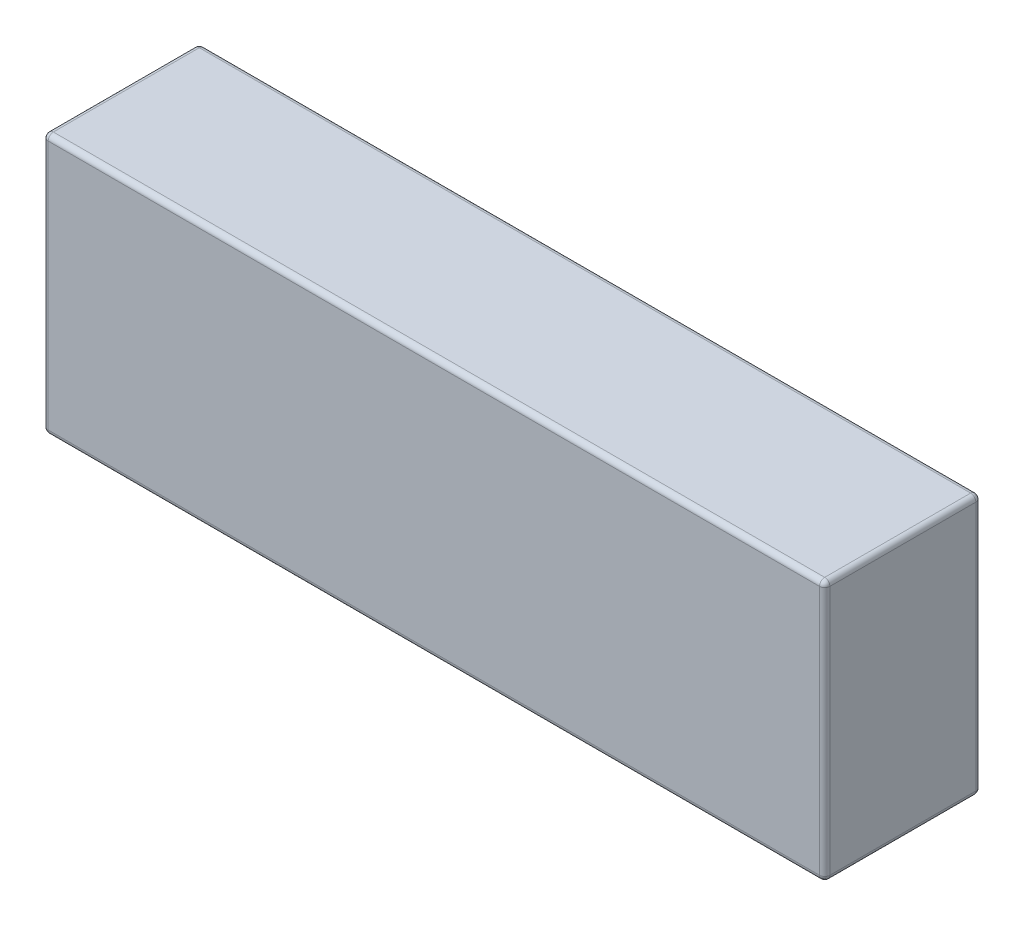
SolidWorks part; units mm, degrees
material "Maple"
ref_plane "Front Plane" through (0, 0, 0) normal (0, 0, 1) x (1, 0, 0)
ref_plane "Top Plane" through (0, 0, 0) normal (0, 1, 0) x (1, 0, 0)
ref_plane "Right Plane" through (0, 0, 0) normal (1, 0, 0) x (0, 0, -1)
sketch "Sketch1" plane through (0, 0, 0) normal (0, 0, 1) x (1, 0, 0)
  line L1 (-75, 25) -> (75, 25)
  line L2 (-75, 25) -> (-75, -25)
  line L3 (-75, -25) -> (75, -25)
  line L4 (75, 25) -> (75, -25)
  line L5 (-75, 25) -> (75, -25) construction
  line L6 (-75, -25) -> (75, 25) construction
  point P0 (0, 0)
  dimension "D1" = 50
  dimension "D2" = 150
extrude "Boss-Extrude1" add sketch "Sketch1" along normal blind 28
sketch "Sketch3" plane through (0, 0, 28) normal (0, 0, 1) x (1, 0, 0)
  line L1 (-75, 25) -> (75, 25)
  line L2 (-75, 25) -> (-75, -25)
  line L3 (-75, -25) -> (75, -25)
  line L4 (75, 25) -> (75, -25)
  line L5 (-75, 25) -> (75, -25) construction
  line L6 (-75, -25) -> (75, 25) construction
  point P0 (0, 0)
extrude "Boss-Extrude2" add sketch "Sketch3" along normal blind 1
sketch "Sketch4" plane through (0, 0, 0) normal (0, 0, -1) x (-1, 0, 0)
  line L1 (-75, 25) -> (75, 25)
  line L2 (-75, 25) -> (-75, -25)
  line L3 (-75, -25) -> (75, -25)
  line L4 (75, 25) -> (75, -25)
  line L5 (-75, 25) -> (75, -25) construction
  line L6 (-75, -25) -> (75, 25) construction
  point P0 (0, 0)
extrude "Boss-Extrude3" add sketch "Sketch4" along normal blind 1
fillet "Fillet1" radius 1 12 edges at (-75, 25, 14) (-75, -25, 14) (75, -25, 14) (0, -25, 29) (-75, 0, 29) (0, -25, -1) (75, 0, -1) (0, 25, -1) (-75, 0, -1) (75, 25, 14) (0, 25, 29) (75, 0, 29)
sketch "Sketch5" plane through (0, 0, -1) normal (0, 0, -1) x (-1, 0, 0)
  line L0 (-92.6765, 14.1347) -> (-92.6765, 169.4681) construction
sketch "Sketch6" plane through (0, 0, 29) normal (0, 0, 1) x (1, 0, 0)
  line L0 (13.3076, 93.2758) -> (166.641, 93.2758) construction
sketch "Sketch7" plane through (0, 0, -1) normal (0, 0, -1) x (-1, 0, 0)
  line L0 (0, 25) -> (0, -25)
  line L1 (-74, 25) -> (74, 25) construction
  line L2 (74, -25) -> (-74, -25) construction
  line L4 (-25, 25) -> (25, 25)
  line L5 (-25, 25) -> (-25, -25)
  line L6 (-25, -25) -> (25, -25)
  line L7 (25, 25) -> (25, -25)
  line L8 (-25, 25) -> (25, -25) construction
  line L9 (-25, -25) -> (25, 25) construction
  point P6 (0, 0)
  dimension "D1" = 50
